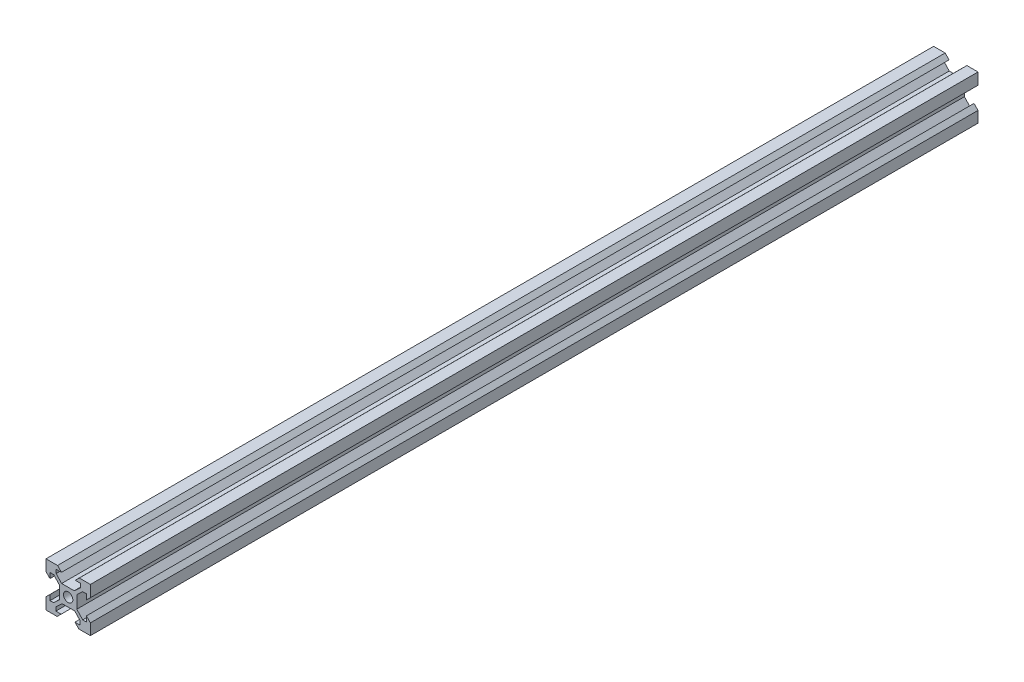
SolidWorks part; units mm, degrees
ref_plane "Płaszczyzna przednia" through (0, 0, 0) normal (0, 0, 1) x (1, 0, 0)
ref_plane "Płaszczyzna górna" through (0, 0, 0) normal (0, 1, 0) x (1, 0, 0)
ref_plane "Płaszczyzna prawa" through (0, 0, 0) normal (1, 0, 0) x (0, 0, -1)
sketch "Szkic1" plane through (0, 0, 0) normal (0, 0, 1) x (1, 0, 0)
  line L0 (7.0398, 13.8855) -> (12.7198, 13.8855)
  line L1 (0, 0) -> (5, 0)
  line L2 (0, 0) -> (0, 5.1987)
  line L3 (0, 20) -> (5.1987, 20)
  line L4 (20, 0) -> (20, 5)
  line L6 (6.9691, 18.1996) -> (5.1987, 20)
  line L7 (13.1691, 18.1996) -> (15, 20)
  line L9 (15, 20) -> (20, 20)
  line L10 (4.5691, 18.1996) -> (6.9691, 18.1996)
  line L11 (4.5691, 18.1996) -> (4.5691, 16.5388)
  line L12 (15.5691, 18.1996) -> (15.5691, 16.5388)
  line L13 (0, 10) -> (20, 10) construction
  line L14 (4.5691, 16.5388) -> (7.0398, 13.8855)
  line L15 (12.7198, 13.8855) -> (15.5691, 16.5388)
  line L16 (13.1691, 18.1996) -> (15.5691, 18.1996)
  line L17 (18.1996, 13.0309) -> (20, 14.8013)
  line L18 (18.1996, 15.4309) -> (18.1996, 13.0309)
  line L19 (18.1996, 15.4309) -> (16.5388, 15.4309)
  line L20 (16.5388, 15.4309) -> (13.8855, 12.9602)
  line L21 (13.8855, 12.9602) -> (13.8855, 7.2802)
  line L22 (13.8855, 7.2802) -> (16.5388, 4.4309)
  line L23 (18.1996, 4.4309) -> (16.5388, 4.4309)
  line L24 (18.1996, 6.8309) -> (18.1996, 4.4309)
  line L25 (18.1996, 6.8309) -> (20, 5)
  line L26 (13.0309, 1.8004) -> (14.8013, 0)
  line L27 (15.4309, 1.8004) -> (13.0309, 1.8004)
  line L28 (15.4309, 1.8004) -> (15.4309, 3.4612)
  line L29 (15.4309, 3.4612) -> (12.9602, 6.1145)
  line L30 (12.9602, 6.1145) -> (7.2802, 6.1145)
  line L31 (7.2802, 6.1145) -> (4.4309, 3.4612)
  line L32 (4.4309, 1.8004) -> (4.4309, 3.4612)
  line L33 (6.8309, 1.8004) -> (4.4309, 1.8004)
  line L34 (6.8309, 1.8004) -> (5, 0)
  line L35 (1.8004, 6.9691) -> (0, 5.1987)
  line L36 (1.8004, 4.5691) -> (1.8004, 6.9691)
  line L37 (1.8004, 4.5691) -> (3.4612, 4.5691)
  line L38 (3.4612, 4.5691) -> (6.1145, 7.0398)
  line L39 (6.1145, 7.0398) -> (6.1145, 12.7198)
  line L40 (6.1145, 12.7198) -> (3.4612, 15.5691)
  line L41 (1.8004, 15.5691) -> (3.4612, 15.5691)
  line L42 (1.8004, 13.1691) -> (1.8004, 15.5691)
  line L43 (1.8004, 13.1691) -> (0, 15)
  line L44 (0, 15) -> (0, 20)
  line L45 (14.8013, 0) -> (20, 0)
  line L46 (20, 14.8013) -> (20, 20)
  circle A0 centre (10, 10) radius 2.1
  dimension "D3" = 6.2
  dimension "D1" = 20
  dimension "D2" = 20
  dimension "D4" = 2.4
  dimension "D5" = 2.4
  dimension "D6" = 360
  dimension "D7" = 1.4716
  dimension "D8" = 90
  dimension "D9" = 5.68
  dimension "D19" = 4
extrude "Dodanie-wyciągnięcie1" add sketch "Szkic1" along normal blind 400
